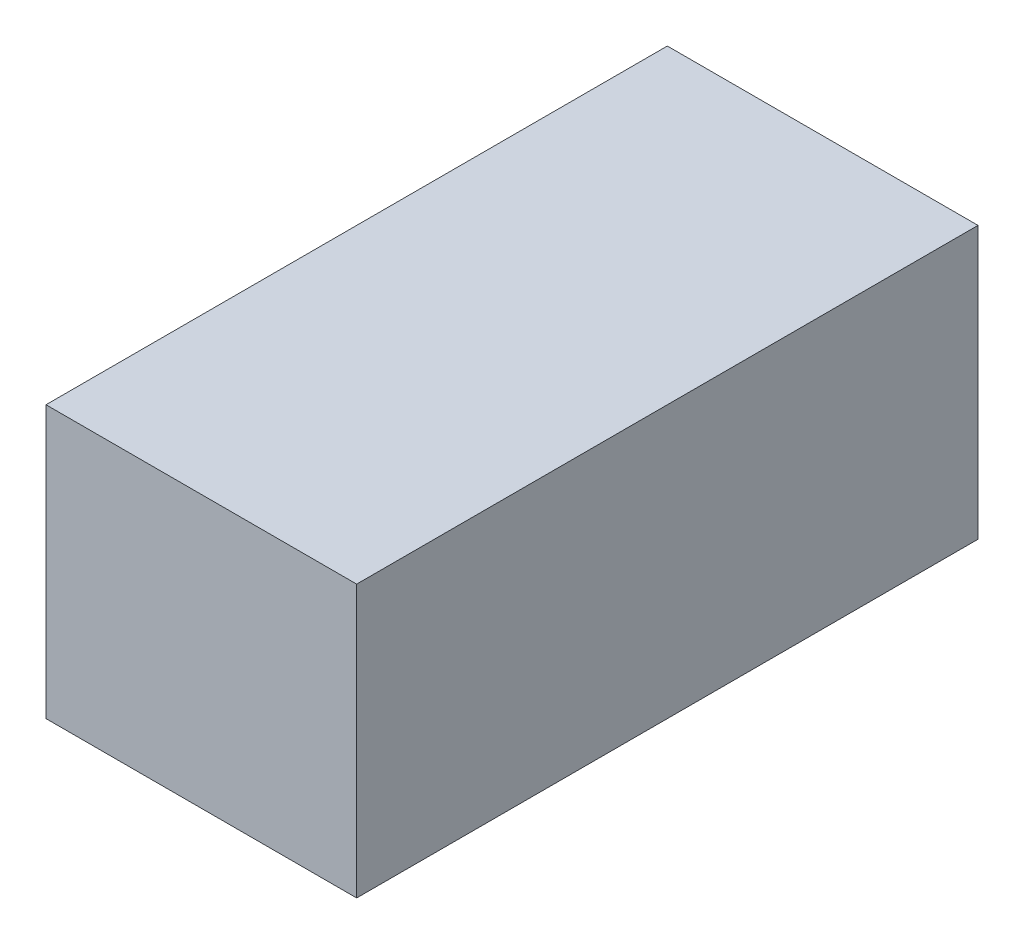
SolidWorks part; units mm, degrees
material "ABS"
ref_plane "Alzado" through (0, 0, 0) normal (0, 0, 1) x (1, 0, 0)
ref_plane "Planta" through (0, 0, 0) normal (0, 1, 0) x (1, 0, 0)
ref_plane "Vista lateral" through (0, 0, 0) normal (1, 0, 0) x (0, 0, -1)
sketch "Sketch1" plane through (0, 0, 0) normal (0, 0, 1) x (1, 0, 0)
  line L1 (-20, -17.5) -> (20, -17.5)
  line L2 (-20, -17.5) -> (-20, 17.5)
  line L3 (-20, 17.5) -> (20, 17.5)
  line L4 (20, -17.5) -> (20, 17.5)
  line L5 (-20, -17.5) -> (20, 17.5) construction
  line L6 (-20, 17.5) -> (20, -17.5) construction
  point P0 (0, 0)
  dimension "D1" = 35
  dimension "D2" = 40
extrude "Boss-Extrude1" add sketch "Sketch1" along normal blind 80
